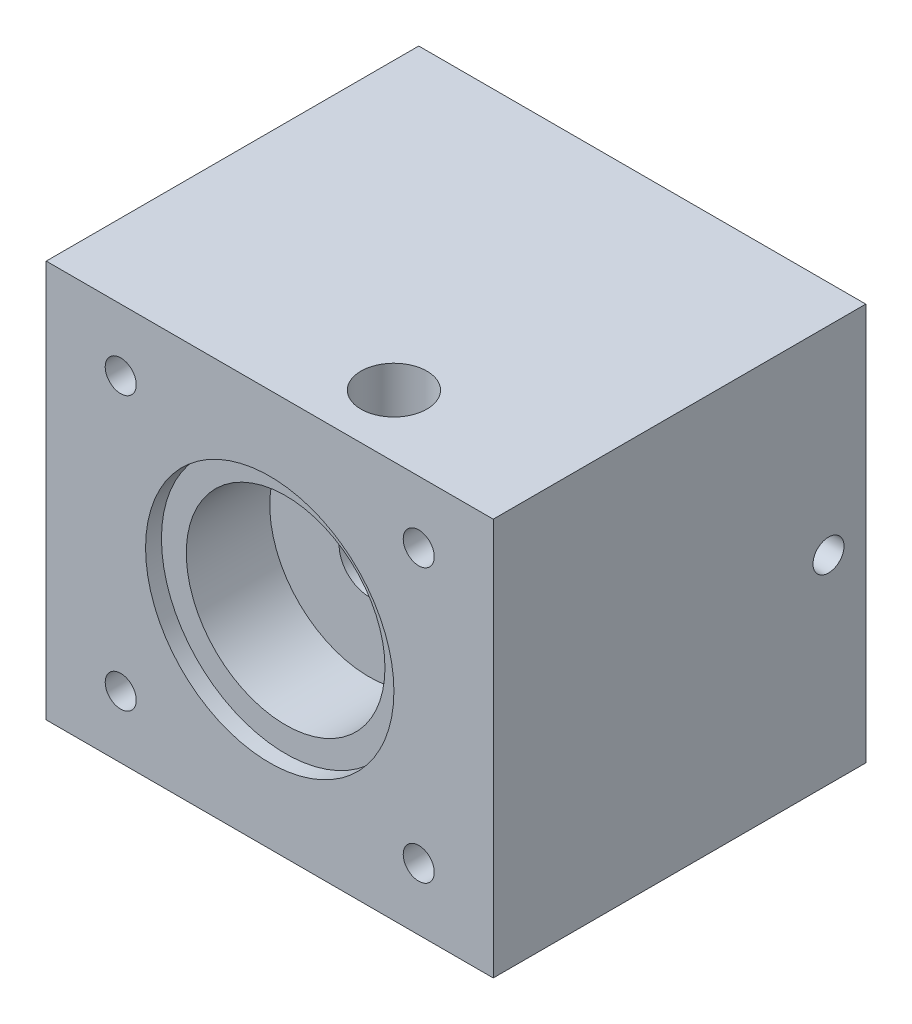
SolidWorks part; units mm, degrees
ref_plane "Front Plane" through (0, 0, 0) normal (0, 0, 1) x (1, 0, 0)
ref_plane "Top Plane" through (0, 0, 0) normal (0, 1, 0) x (1, 0, 0)
ref_plane "Right Plane" through (0, 0, 0) normal (1, 0, 0) x (0, 0, -1)
sketch "Sketch1" plane through (0, 0, 0) normal (0, 0, 1) x (1, 0, 0)
  line L1 (0, 0) -> (57.15, 0)
  line L2 (0, 0) -> (0, 50.8)
  line L3 (0, 50.8) -> (57.15, 50.8)
  line L4 (57.15, 0) -> (57.15, 50.8)
  dimension "D1" = 50.8
  dimension "D2" = 57.15
extrude "Boss-Extrude1" add sketch "Sketch1" along normal blind 47.625
sketch "Sketch2" plane through (0, 0, 47.625) normal (0, 0, 1) x (1, 0, 0)
  line L0 (57.15, 0) -> (57.15, 50.8) construction
  line L1 (57.15, 50.8) -> (0, 50.8) construction
  circle A0 centre (28.575, 25.4) radius 3.8354
  dimension "D1" = 7.6708
  dimension "D2" = 28.575
  dimension "D3" = 25.4
extrude "Cut-Extrude1" cut sketch "Sketch2" against normal through all
sketch "Sketch3" plane through (0, 0, 47.625) normal (0, 0, 1) x (1, 0, 0)
  line L0 (57.15, 0) -> (57.15, 50.8) construction
  line L1 (57.15, 50.8) -> (0, 50.8) construction
  circle A0 centre (28.575, 25.4) radius 12.7
  point P4 (0, 0)
  point P6 (28.575, 25.4)
  dimension "D1" = 25.4
  dimension "D2" = 28.575
  dimension "D3" = 25.4
extrude "Cut-Extrude2" cut sketch "Sketch3" against normal blind 12.7
sketch "Sketch4" plane through (0, 0, 47.625) normal (0, 0, 1) x (1, 0, 0)
  line L0 (57.15, 0) -> (57.15, 50.8) construction
  line L1 (57.15, 50.8) -> (0, 50.8) construction
  circle A0 centre (28.575, 25.4) radius 15.875
  dimension "D1" = 31.75
  dimension "D2" = 28.575
  dimension "D3" = 25.4
extrude "Cut-Extrude3" cut sketch "Sketch4" against normal blind 2.032
sketch "Sketch5" plane through (0, 50.8, 0) normal (0, 1, 0) x (1, 0, 0)
  line L0 (57.15, -47.625) -> (57.15, 0) construction
  line L1 (57.15, -47.625) -> (0, -47.625) construction
  circle A0 centre (36.5125, -39.6875) radius 4.2164
  dimension "D1" = 8.4328
  dimension "D2" = 20.6375
  dimension "D3" = 7.9375
extrude "Cut-Extrude4" cut sketch "Sketch5" against normal blind 25.4
sketch "Sketch6" plane through (0, 0, 0) normal (0, 0, -1) x (-1, 0, 0)
  line L0 (0, 50.8) -> (0, 0) construction
  line L1 (-57.15, 50.8) -> (0, 50.8) construction
  circle A0 centre (-28.575, 25.4) radius 6.35
  point P6 (-28.575, 50.8)
  dimension "D1" = 12.7
  dimension "D2" = 28.575
  dimension "D3" = 25.4
extrude "Cut-Extrude5" cut sketch "Sketch6" against normal blind 2.794
sketch "Sketch7" plane through (0, 0, 0) normal (0, 0, -1) x (-1, 0, 0)
  line L0 (-57.15, 0) -> (-57.15, 50.8) construction
  line L1 (0, 0) -> (-57.15, 0) construction
  line L2 (0, 50.8) -> (0, 0) construction
  circle A0 centre (-9.525, 25.4) radius 1.985
  circle A1 centre (-47.625, 25.4) radius 1.985
  dimension "D1" = 3.97
  dimension "D2" = 3.97
  dimension "D3" = 9.525
  dimension "D4" = 25.4
  dimension "D5" = 9.525
  dimension "D6" = 25.4
extrude "Cut-Extrude6" cut sketch "Sketch7" against normal blind 6.35
sketch "Sketch8" plane through (0, 0, 0) normal (0, 0, -1) x (-1, 0, 0)
  line L0 (-57.15, 0) -> (-57.15, 50.8) construction
  line L1 (0, 50.8) -> (0, 0) construction
  line L2 (-57.15, 50.8) -> (0, 50.8) construction
  line L3 (0, 0) -> (-57.15, 0) construction
  circle A0 centre (-47.625, 42.8625) radius 1.985
  circle A1 centre (-9.525, 42.8625) radius 1.985
  circle A2 centre (-9.525, 7.9375) radius 1.985
  circle A3 centre (-47.625, 7.9375) radius 1.985
  dimension "D1" = 3.97
  dimension "D2" = 3.97
  dimension "D3" = 3.97
  dimension "D4" = 3.97
  dimension "D5" = 9.525
  dimension "D6" = 9.525
  dimension "D7" = 9.525
  dimension "D8" = 9.525
  dimension "D9" = 7.9375
  dimension "D10" = 7.9375
  dimension "D11" = 7.9375
  dimension "D12" = 7.9375
extrude "Cut-Extrude7" cut sketch "Sketch8" against normal through all
sketch "Sketch9" plane through (0, 0, 0) normal (-1, 0, 0) x (0, 0, 1)
  line L1 (47.625, 0) -> (0, 0) construction
  line L2 (0, 50.8) -> (0, 0) construction
  circle A0 centre (4.7625, 25.4) radius 1.985
  dimension "D1" = 3.97
  dimension "D2" = 4.7625
  dimension "D3" = 25.4
extrude "Cut-Extrude9" cut sketch "Sketch9" against normal blind 11.1125
sketch "Sketch10" plane through (57.15, 0, 0) normal (1, 0, 0) x (0, 0, -1)
  line L0 (-47.625, 0) -> (0, 0) construction
  line L1 (0, 0) -> (0, 50.8) construction
  circle A0 centre (-4.7625, 25.4) radius 1.985
  dimension "D1" = 3.97
  dimension "D2" = 25.4
  dimension "D3" = 4.7625
extrude "Cut-Extrude10" cut sketch "Sketch10" against normal blind 11.1125
